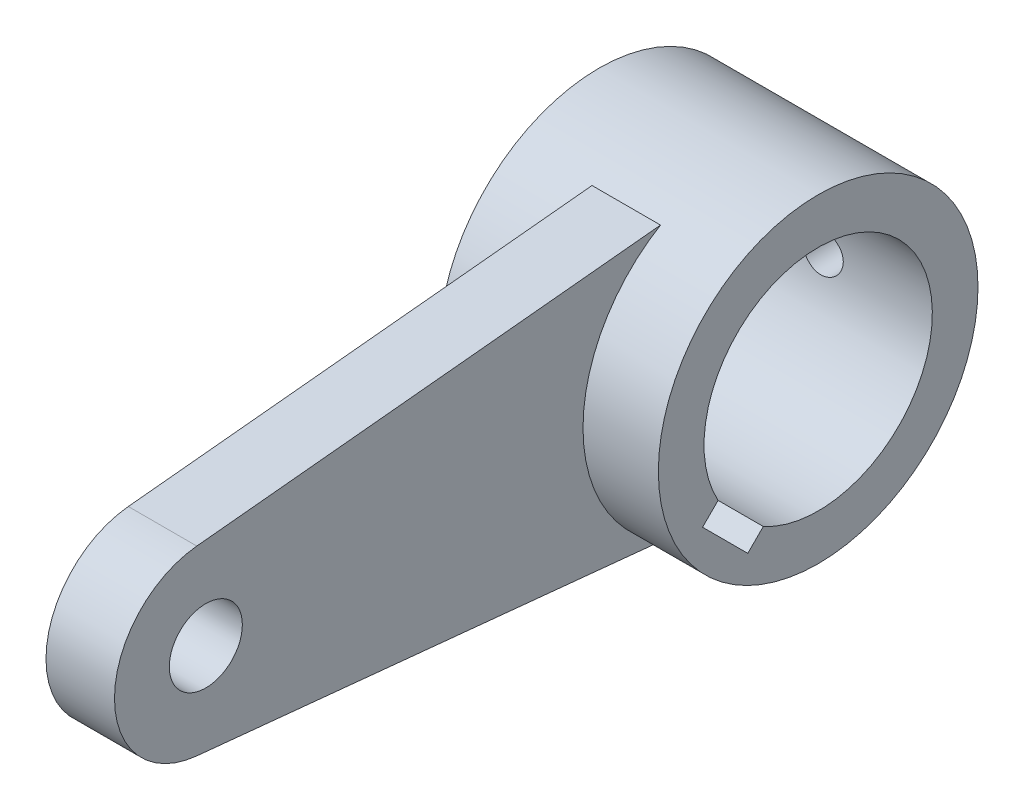
SolidWorks part; units mm, degrees
material "ASTM A36 Steel"
ref_plane "Front Plane" through (0, 0, 0) normal (0, 0, 1) x (1, 0, 0)
ref_plane "Top Plane" through (0, 0, 0) normal (0, 1, 0) x (1, 0, 0)
ref_plane "Right Plane" through (0, 0, 0) normal (1, 0, 0) x (0, 0, -1)
sketch "Sketch1" plane through (0, 0, 0) normal (1, 0, 0) x (0, 0, -1)
  circle A0 centre (0, 0) radius 25
  circle A1 centre (0, 0) radius 35
  dimension "D1" = 50
  dimension "D2" = 70
extrude "Boss-Extrude1" add sketch "Sketch1" along normal mid plane 48
sketch "Sketch2" plane through (0, 0, 0) normal (1, 0, 0) x (0, 0, -1)
  line L0 (-18.0278, 30) -> (-119.579, 19.9018)
  line L1 (-119.579, -19.9018) -> (-18.0278, -30)
  circle A0 centre (0, 0) radius 35 construction
  arc A1 (-119.579, 19.9018) -> (-119.579, -19.9018) centre (-117.6, 0) ccw
  circle A3 centre (0, 0) radius 35
  arc A4 (-18.0278, 30) -> (-18.0278, -30) centre (0, 0) ccw
  dimension "D2" = 20
  dimension "D1" = 117.6
  dimension "D3" = 60
  dimension "D4" = 0
extrude "Boss-Extrude2" add sketch "Sketch2" along normal mid plane 15
sketch "Sketch3" plane through (7.5, 0, 0) normal (1, 0, 0) x (0, 0, -1)
  circle A0 centre (-117.6, 0) radius 8
  dimension "D1" = 16
extrude "Cut-Extrude1" cut sketch "Sketch3" against normal blind 15
sketch "Sketch5" plane through (24, 0, 0) normal (1, 0, 0) x (0, 0, -1)
  line L0 (-3.7029, 6.1966) -> (-25.3144, -15.4149)
  line L1 (-3.7029, 6.1966) -> (6.1966, -3.7029)
  line L2 (-25.3144, -15.4149) -> (-15.4149, -25.3144)
  line L3 (6.1966, -3.7029) -> (-15.4149, -25.3144)
  line L4 (-20.3647, -20.3647) -> (1.2469, 1.2469) construction
  line L5 (-117.6, 0) -> (0, 0) construction
  dimension "D1" = 28.8
  dimension "D2" = 14
  dimension "D3" = 45
extrude "Cut-Extrude2" cut sketch "Sketch5" against normal through all
ref_plane "Plane1" through (0, 0, -35) normal (0, 0, 1) x (1, 0, 0)
sketch "Sketch6" plane through (0, 0, -35) normal (0, 0, 1) x (1, 0, 0)
  circle A0 centre (0, 0) radius 4.5
  dimension "D1" = 9
extrude "Cut-Extrude3" cut sketch "Sketch6" along normal blind 24
